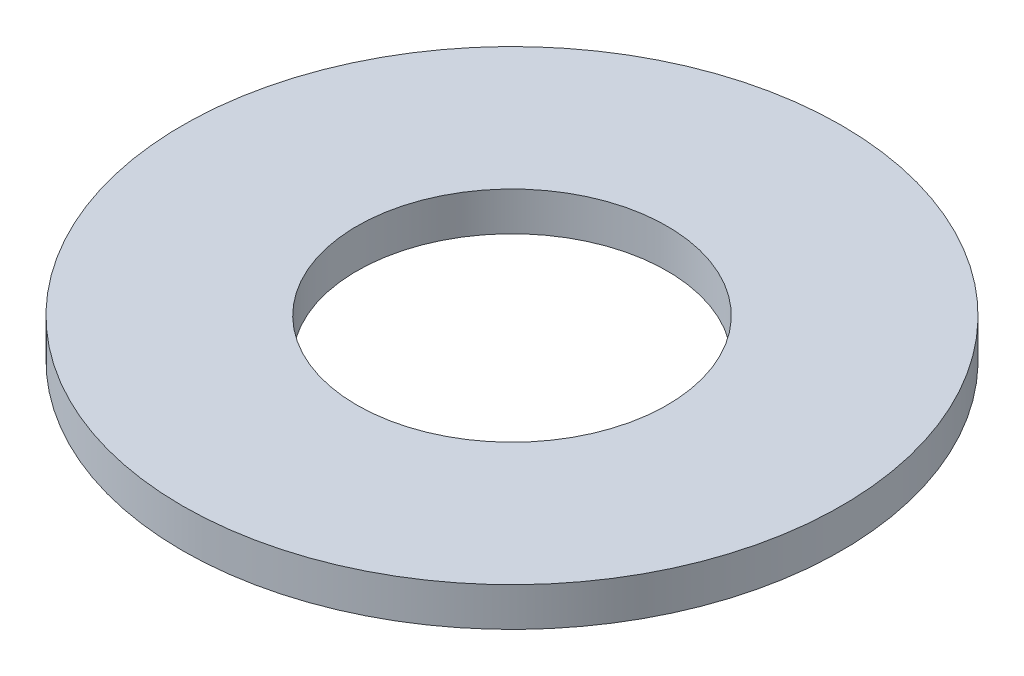
SolidWorks part; units mm, degrees
ref_plane "Front Plane" through (0, 0, 0) normal (0, 0, 1) x (1, 0, 0)
ref_plane "Top Plane" through (0, 0, 0) normal (0, 1, 0) x (1, 0, 0)
ref_plane "Right Plane" through (0, 0, 0) normal (1, 0, 0) x (0, 0, -1)
sketch "Sketch1" plane through (0, 0, 0) normal (0, 1, 0) x (1, 0, 0)
  circle A0 centre (0, 0) radius 17
  circle A1 centre (0, 0) radius 8
  dimension "D1" = 34
  dimension "D2" = 16
extrude "Boss-Extrude1" add sketch "Sketch1" along normal blind 2
